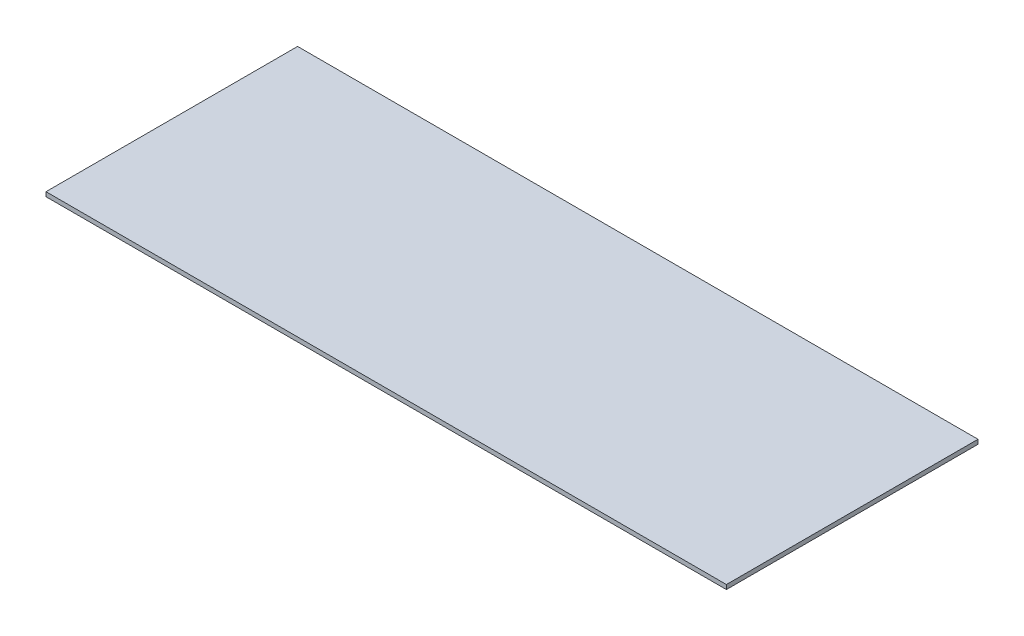
SolidWorks part; units mm, degrees
ref_plane "Front Plane" through (0, 0, 0) normal (0, 0, 1) x (1, 0, 0)
ref_plane "Top Plane" through (0, 0, 0) normal (0, 1, 0) x (1, 0, 0)
ref_plane "Right Plane" through (0, 0, 0) normal (1, 0, 0) x (0, 0, -1)
sketch "Sketch1" plane through (0, 0, 0) normal (0, 1, 0) x (1, 0, 0)
  line L1 (0, 0) -> (311, 0)
  line L2 (0, 0) -> (0, 115)
  line L3 (0, 115) -> (311, 115)
  line L4 (311, 0) -> (311, 115)
  dimension "D1" = 311
  dimension "D2" = 115
extrude "Boss-Extrude1" add sketch "Sketch1" along normal blind 2
